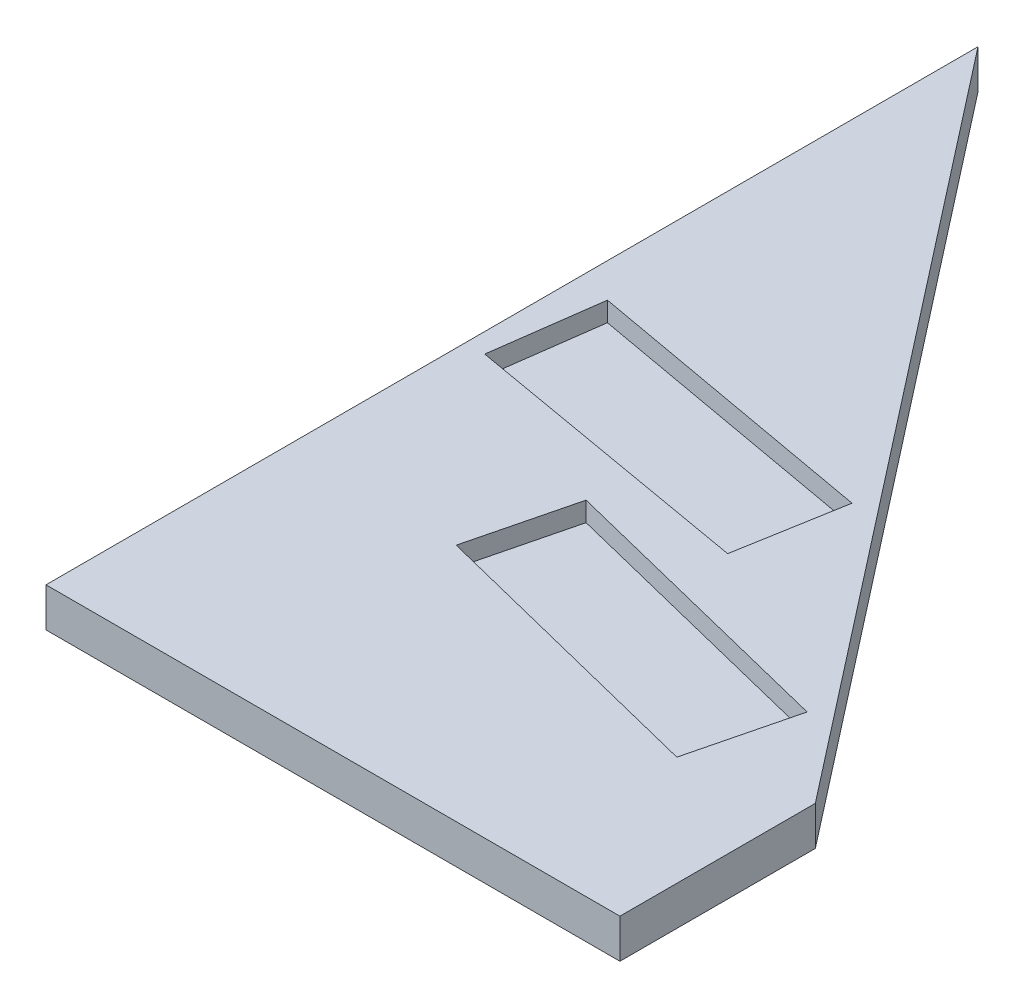
SolidWorks part; units mm, degrees
ref_plane "Front Plane" through (0, 0, 0) normal (0, 0, 1) x (1, 0, 0)
ref_plane "Top Plane" through (0, 0, 0) normal (0, 1, 0) x (1, 0, 0)
ref_plane "Right Plane" through (0, 0, 0) normal (1, 0, 0) x (0, 0, -1)
sketch "Sketch1" plane through (0, 0, 0) normal (0, 1, 0) x (1, 0, 0)
  line L0 (-25, 50.39) -> (33.74, -25)
  line L6 (-25, 50.39) -> (-25, -45)
  line L7 (-55, 0) -> (55, 0) construction
  line L10 (-25, -45) -> (33.74, -45)
  line L11 (33.74, -25) -> (33.74, -45)
  line L12 (0, -55) -> (0, 55) construction
  point P0 (0, 0)
  dimension "D1" = 95.39
  dimension "D2" = 25
  dimension "D3" = 58.74
  dimension "D4" = 45
  dimension "D5" = 20
extrude "Boss-Extrude1" add sketch "Sketch1" along normal blind 4
sketch "Sketch2" plane through (0, 4, 0) normal (0, 1, 0) x (1, 0, 0)
  line L1 (-23, -2.0971) -> (7.1217, -7.3542)
  line L2 (-23, -2.0971) -> (-21.499, 8.9615)
  line L3 (-21.499, 8.9615) -> (9.0129, 3.482)
  line L4 (7.1217, -7.3542) -> (9.0129, 3.482)
  line L5 (-23, -2.0971) -> (9.0129, 3.482) construction
  line L6 (-21.499, 8.9615) -> (7.1217, -7.3542) construction
  line L8 (-25, 50.39) -> (-25, -45) construction
  line L9 (33.74, -25) -> (-25, 50.39) construction
  line L10 (-25, -45) -> (33.74, -45) construction
  point P0 (-6.9935, 0.6924)
  point P6 (0, 0)
  dimension "D1" = 11
  dimension "D2" = 31
  dimension "D3" = 99.9
  dimension "D4" = 2
  dimension "D5" = 2
  dimension "D6" = 45.6924
extrude "Cut-Extrude1" cut sketch "Sketch2" against normal blind 2
sketch "Sketch4" plane through (0, 4, 0) normal (0, 1, 0) x (1, 0, 0)
  line L0 (-25, 50.39) -> (-25, -45) construction
  line L1 (-4.8679, -9.8542) -> (25.22, -17.319)
  line L2 (-4.8679, -9.8542) -> (-7.5204, -20.4927)
  line L3 (-7.5204, -20.4927) -> (22.5588, -27.9923)
  line L4 (25.22, -17.319) -> (22.5588, -27.9923)
  line L5 (-4.8679, -9.8542) -> (22.5588, -27.9923) construction
  line L6 (-7.5204, -20.4927) -> (25.22, -17.319) construction
  line L7 (33.74, -25) -> (-25, 50.39) construction
  line L8 (-25, -45) -> (33.74, -45) construction
  point P0 (8.8231, -18.9084)
  dimension "D1" = 31
  dimension "D2" = 11
  dimension "D3" = 104
  dimension "D4" = 2
  dimension "D5" = 17.4796
  dimension "D6" = 17.0077
  dimension "D7" = 2.5
extrude "Cut-Extrude2" cut sketch "Sketch4" against normal blind 2
